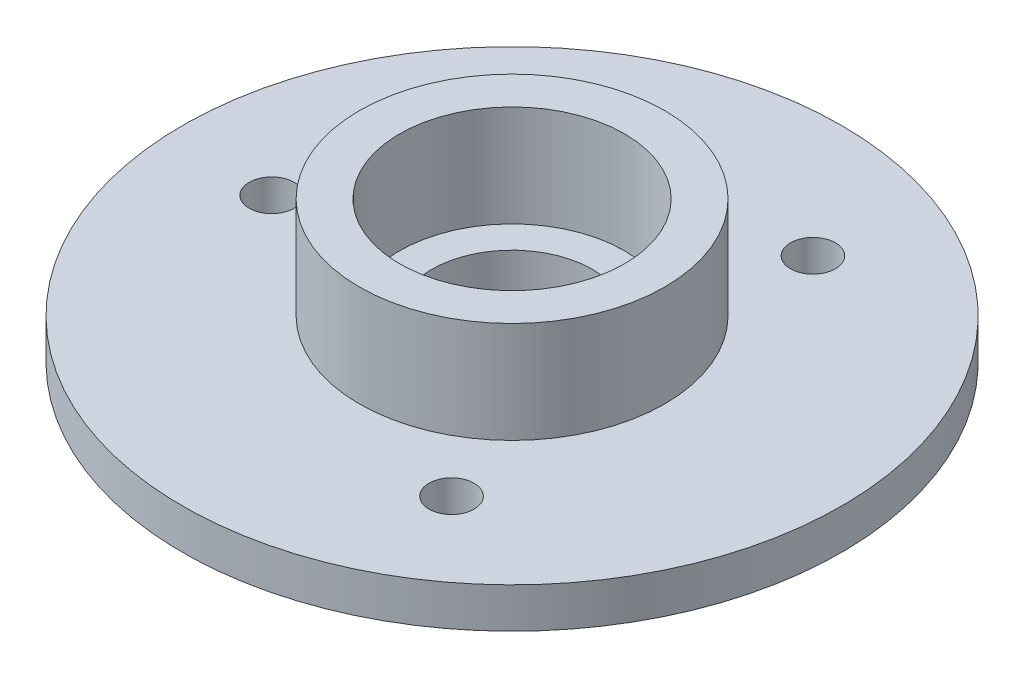
SolidWorks part; units mm, degrees
ref_plane "Plan de face" through (0, 0, 0) normal (0, 0, 1) x (1, 0, 0)
ref_plane "Plan de dessus" through (0, 0, 0) normal (0, 1, 0) x (1, 0, 0)
ref_plane "Plan de droite" through (0, 0, 0) normal (1, 0, 0) x (0, 0, -1)
sketch "Esquisse1" plane through (0, 0, 0) normal (0, 0, 1) x (1, 0, 0)
  line L0 (0, 0) -> (0, 5.0644) construction
  line L1 (5, 0) -> (20.5, 0)
  line L2 (5, 0) -> (5, 2.5)
  line L3 (5, 2.5) -> (20.5, 2.5)
  line L4 (20.5, 0) -> (20.5, 2.5)
  line L5 (9.5, 2.5) -> (12, 2.5)
  line L7 (9.5, 2.5) -> (7, 2.5)
  line L8 (9.5, 2.5) -> (9.5, 8.8)
  line L9 (9.5, 8.8) -> (7, 8.8)
  line L10 (7, 2.5) -> (7, 8.8)
  dimension "D1" = 5
  dimension "D2" = 20.5
  dimension "D3" = 2.5
  dimension "D4" = 15.5
  dimension "D5" = 9.5
  dimension "D6" = 2.5
  dimension "D7" = 6.3
revolve "Révolution1" add sketch "Esquisse1" angle 360 about L0
sketch "Esquisse2" plane through (0, 0, 0) normal (0, -1, 0) x (1, 0, 0)
  circle A0 centre (-13.9652, 0.9862) radius 1.4
  circle A1 centre (7.8367, 11.6012) radius 1.4
  circle A2 centre (6.1286, -12.5873) radius 1.4
  dimension "D2" = 2.8
  dimension "D1" = 14
extrude "Extrusion1" cut sketch "Esquisse2" against normal blind 10
